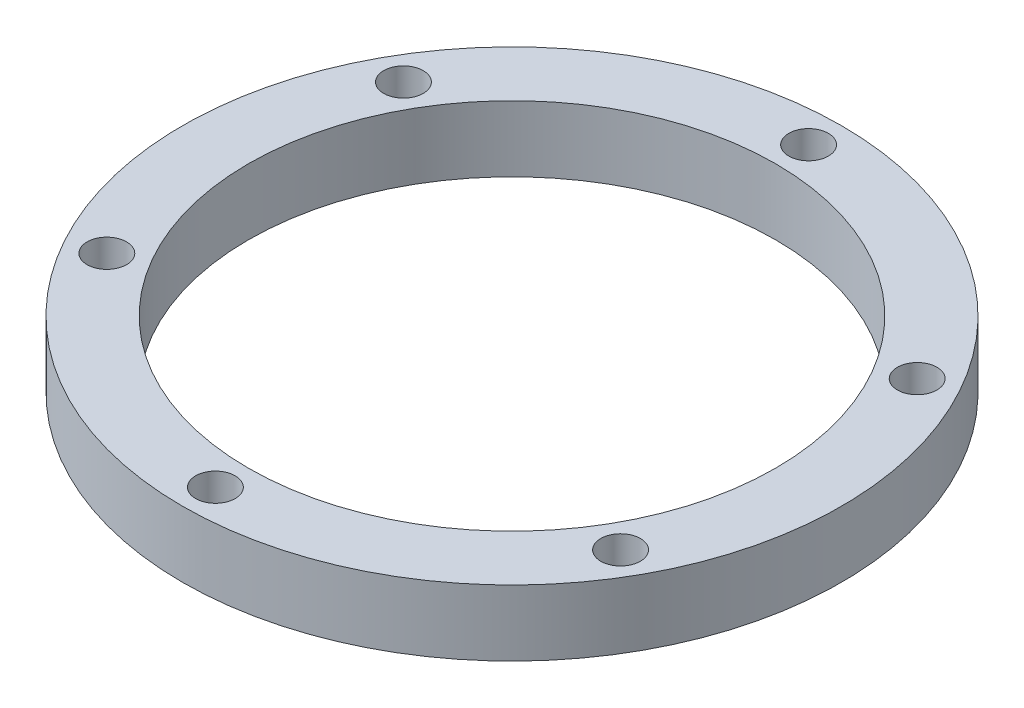
SolidWorks part; units mm, degrees
ref_plane "Front Plane" through (0, 0, 0) normal (0, 0, 1) x (1, 0, 0)
ref_plane "Top Plane" through (0, 0, 0) normal (0, 1, 0) x (1, 0, 0)
ref_plane "Right Plane" through (0, 0, 0) normal (1, 0, 0) x (0, 0, -1)
sketch "Sketch2" plane through (0, 0, 0) normal (0, 1, 0) x (1, 0, 0)
  circle A0 centre (0, 0) radius 50
  circle A1 centre (0, 0) radius 40
  dimension "D1" = 100
  dimension "D2" = 80
extrude "Boss-Extrude1" add sketch "Sketch2" along normal blind 10
sketch "Sketch3" plane through (0, 10, 0) normal (0, 1, 0) x (1, 0, 0)
  line L0 (0, 87.7291) -> (0, -95.3404) construction
  line L1 (0, 0) -> (43301.2702, 25000) construction
  line L2 (0, 0) -> (-43301.2702, 25000) construction
  circle A0 centre (0, 45) radius 3
  circle A1 centre (38.9711, 22.5) radius 3
  circle A2 centre (38.9711, -22.5) radius 3
  circle A3 centre (0, -45) radius 3
  circle A4 centre (-38.9711, -22.5) radius 3
  circle A5 centre (-38.9711, 22.5) radius 3
  dimension "D3" = 6
  dimension "D5" = 6
  dimension "D7" = 6
  dimension "D9" = 6
  dimension "D11" = 6
  dimension "D13" = 6
  dimension "D1" = 60
  dimension "D2" = 60
  dimension "D4" = 45
  dimension "D6" = 45
  dimension "D8" = 45
  dimension "D10" = 45
  dimension "D12" = 45
  dimension "D14" = 45
sketch "Sketch4" plane through (0, 10, 0) normal (0, 1, 0) x (1, 0, 0)
  line L0 (0, 0) -> (0, -50000) construction
  line L1 (0, 0) -> (50000, 0) construction
  line L2 (0, 0) -> (25000, 43301.2702) construction
  line L3 (0, 0) -> (-25000, 43301.2702) construction
  dimension "D1" = 30
  dimension "D2" = 30
sketch "Sketch9" plane through (0, 0, 0) normal (1, 0, 0) x (0, 0, -1)
  line L0 (0, 0) -> (0, 13.5436) construction
  point P0 (0, 13.5436)
extrude "Cut-Extrude1" cut sketch "Sketch3" against normal blind 38
sketch "Sketch10" plane through (0, 10, 0) normal (0, 1, 0) x (1, 0, 0)
  line L1 (-85.6949, 0) -> (108.1614, 0) construction
  line L2 (0, 0) -> (36.1865, 62.6769) construction
  line L3 (0, 0) -> (31.9555, -55.3485) construction
  line L4 (0, 0) -> (-43.5732, -75.471) construction
  line L5 (0, 0) -> (-45.1912, 78.2734) construction
  dimension "D1" = 60
  dimension "D2" = 60
  dimension "D3" = 60
  dimension "D4" = 60
ref_plane "Plane1" through (0, 5, 0) normal (0, 1, 0) x (1, 0, 0)
sketch "Sketch11" plane through (0, 5, 0) normal (0, 1, 0) x (1, 0, 0)
  point P0 (-38.9711, -22.5)
  point P1 (0, -45)
sketch "Sketch12" plane through (0, 10, 0) normal (0, 1, 0) x (1, 0, 0)
  point P0 (0, -45)
sketch "Sketch13" plane through (0, 10, 0) normal (0, 1, 0) x (1, 0, 0)
  line L0 (-32.9879, -57.1366) -> (32.9879, 57.1366) construction
  line L1 (-93.155, 0) -> (106.2622, 0) construction
  line L2 (-41.784, 72.372) -> (41.784, -72.372) construction
  dimension "D1" = 60
  dimension "D2" = 60
sketch "Sketch14" plane through (0, 10, 0) normal (0, 1, 0) x (1, 0, 0)
  line L0 (0, 68.9972) -> (0, -60.8039) construction
  line L1 (-89.591, 0) -> (97.2394, 0) construction
  line L2 (0, 0) -> (41.1469, 71.2686) construction
  line L3 (0, 0) -> (34.781, -60.2425) construction
  line L4 (0, 0) -> (-43.0171, 74.5078) construction
  line L5 (0, 0) -> (-39.8397, -69.0044) construction
  point P12 (0, 0)
  dimension "D1" = 60
  dimension "D2" = 60
  dimension "D3" = 30
  dimension "D4" = 60
